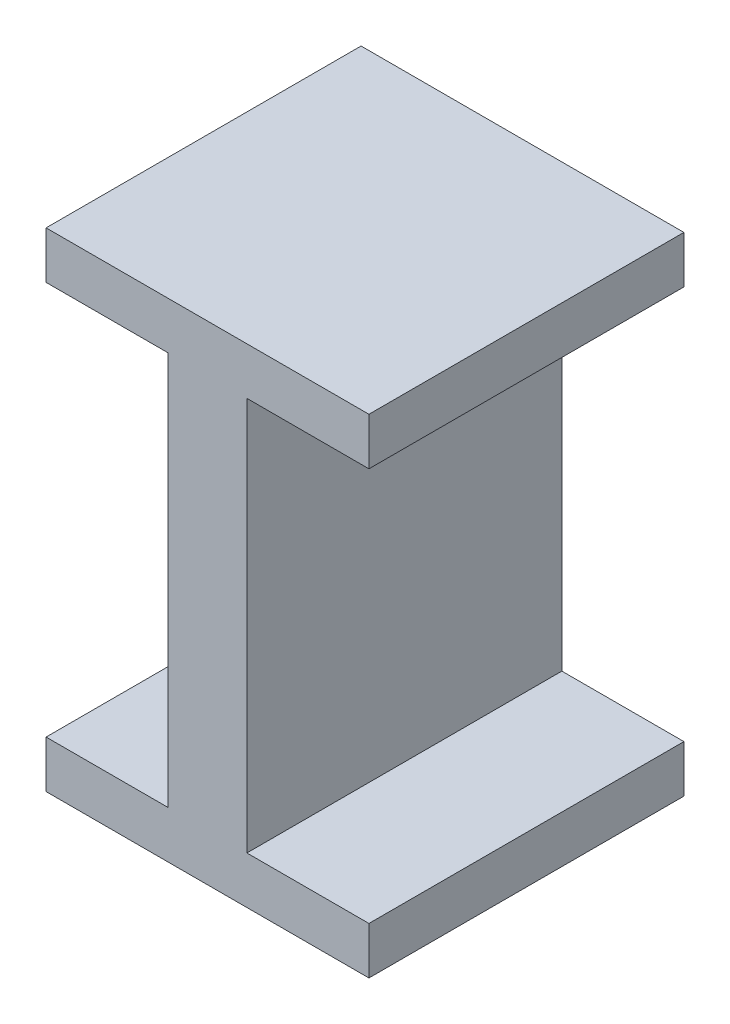
SolidWorks part; units mm, degrees
material "AISI 1010 钢，热轧条材"
ref_plane "前视基准面" through (0, 0, 0) normal (0, 0, 1) x (1, 0, 0)
ref_plane "上视基准面" through (0, 0, 0) normal (0, 1, 0) x (1, 0, 0)
ref_plane "右视基准面" through (0, 0, 0) normal (1, 0, 0) x (0, 0, -1)
sketch "草图1" plane through (0, 0, 0) normal (0, 1, 0) x (1, 0, 0)
  line L1 (-20.5, -20) -> (20.5, -20)
  line L2 (-20.5, -20) -> (-20.5, 20)
  line L3 (-20.5, 20) -> (20.5, 20)
  line L4 (20.5, -20) -> (20.5, 20)
  line L5 (-20.5, -20) -> (20.5, 20) construction
  line L6 (-20.5, 20) -> (20.5, -20) construction
  point P0 (0, 0)
  dimension "D1" = 40
  dimension "D2" = 41
extrude "凸台-拉伸1" add sketch "草图1" along normal blind 6
sketch "草图2" plane through (0, 6, 0) normal (0, 1, 0) x (1, 0, 0)
  line L0 (-20.5, -20) -> (20.5, -20) construction
  line L1 (5, 20) -> (-5, 20)
  line L2 (5, 20) -> (5, -20)
  line L3 (5, -20) -> (-5, -20)
  line L4 (-5, 20) -> (-5, -20)
  line L5 (5, 20) -> (-5, -20) construction
  line L6 (5, -20) -> (-5, 20) construction
  point P0 (0, 0)
  dimension "D1" = 10
extrude "凸台-拉伸2" add sketch "草图2" along normal blind 50
sketch "草图3" plane through (0, 56, 0) normal (0, 1, 0) x (1, 0, 0)
  line L1 (-20.5, 20) -> (20.5, 20)
  line L2 (-20.5, 20) -> (-20.5, -20)
  line L3 (-20.5, -20) -> (20.5, -20)
  line L4 (20.5, 20) -> (20.5, -20)
extrude "凸台-拉伸3" add sketch "草图3" along normal blind 6
